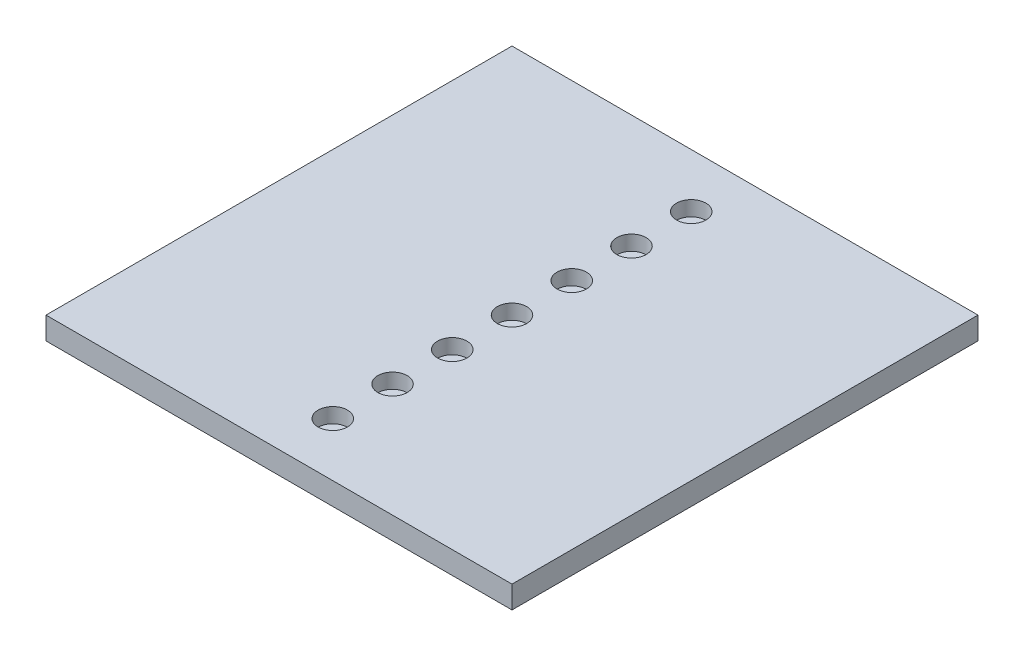
SolidWorks part; units mm, degrees
ref_plane "Front" through (0, 0, 0) normal (0, 0, 1) x (1, 0, 0)
ref_plane "Top" through (0, 0, 0) normal (0, 1, 0) x (1, 0, 0)
ref_plane "Right" through (0, 0, 0) normal (1, 0, 0) x (0, 0, -1)
sketch "Sketch2" plane through (0, 0, 0) normal (0, 1, 0) x (1, 0, 0)
  line L0 (0, 198.12) -> (0, -198.12) construction
  line L1 (-198.12, 198.12) -> (198.12, 198.12)
  line L2 (-198.12, 198.12) -> (-198.12, -198.12)
  line L3 (-198.12, -198.12) -> (198.12, -198.12)
  line L4 (198.12, 198.12) -> (198.12, -198.12)
  line L5 (-198.12, 198.12) -> (198.12, -198.12) construction
  line L6 (-198.12, -198.12) -> (198.12, 198.12) construction
  line L7 (0, 0) -> (0, 50.8) construction
  circle A0 centre (0, 0) radius 3.3782
  circle A1 centre (0, 50.8) radius 3.3782
  circle A2 centre (0, 101.6) radius 3.3782
  circle A3 centre (0, 152.4) radius 3.3782
  circle A4 centre (0, -50.8) radius 3.3782
  circle A5 centre (0, -101.6) radius 3.3782
  circle A6 centre (0, -152.4) radius 3.3782
  point P0 (0, 0)
  point P9 (0, 0)
  dimension "D2" = 6.7564
  dimension "D1" = 396.24
  dimension "D3" = 4
  dimension "D4" = 50.8
  dimension "D5" = 4
extrude "Bolt Holes" add sketch "Sketch2" along normal blind 19.05
sketch "Sketch3" plane through (0, 19.05, 0) normal (0, 1, 0) x (1, 0, 0)
  circle A0 centre (0, -50.8) radius 12.5
  circle A1 centre (0, 0) radius 12.5
  circle A2 centre (0, -101.6) radius 12.5
  circle A3 centre (0, 50.8) radius 12.5
  circle A4 centre (0, 101.6) radius 12.5
  circle A5 centre (0, 152.4) radius 12.5
  circle A6 centre (0, -152.4) radius 12.5
  dimension "D1" = 25
extrude "Counterbore" cut sketch "Sketch3" against normal blind 12.7
